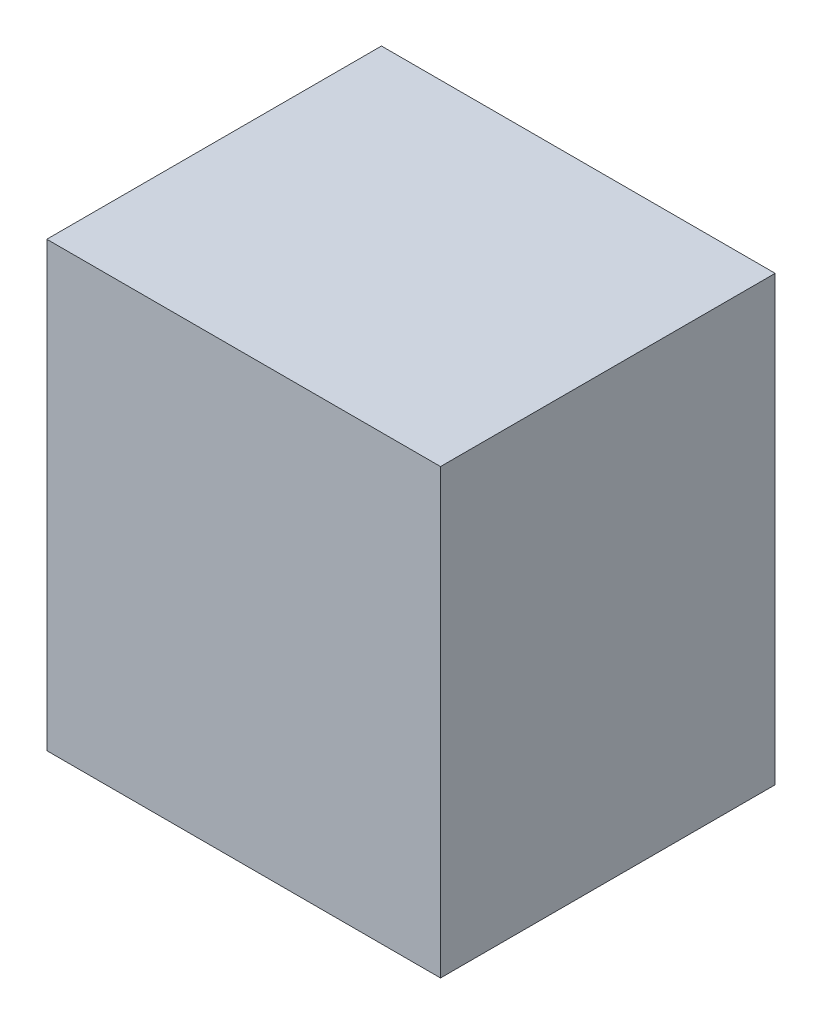
SolidWorks part; units mm, degrees
ref_plane "Front Plane" through (0, 0, 0) normal (0, 0, 1) x (1, 0, 0)
ref_plane "Top Plane" through (0, 0, 0) normal (0, 1, 0) x (1, 0, 0)
ref_plane "Right Plane" through (0, 0, 0) normal (1, 0, 0) x (0, 0, -1)
sketch "Sketch1" plane through (0, 0, 0) normal (0, 0, 1) x (1, 0, 0)
  line L1 (-40, 45) -> (40, 45)
  line L2 (-40, 45) -> (-40, -45)
  line L3 (-40, -45) -> (40, -45)
  line L4 (40, 45) -> (40, -45)
  line L5 (-40, 45) -> (40, -45) construction
  line L6 (-40, -45) -> (40, 45) construction
  point P0 (0, 0)
  dimension "D1" = 80
  dimension "D2" = 90
extrude "Boss-Extrude1" add sketch "Sketch1" along normal blind 68
